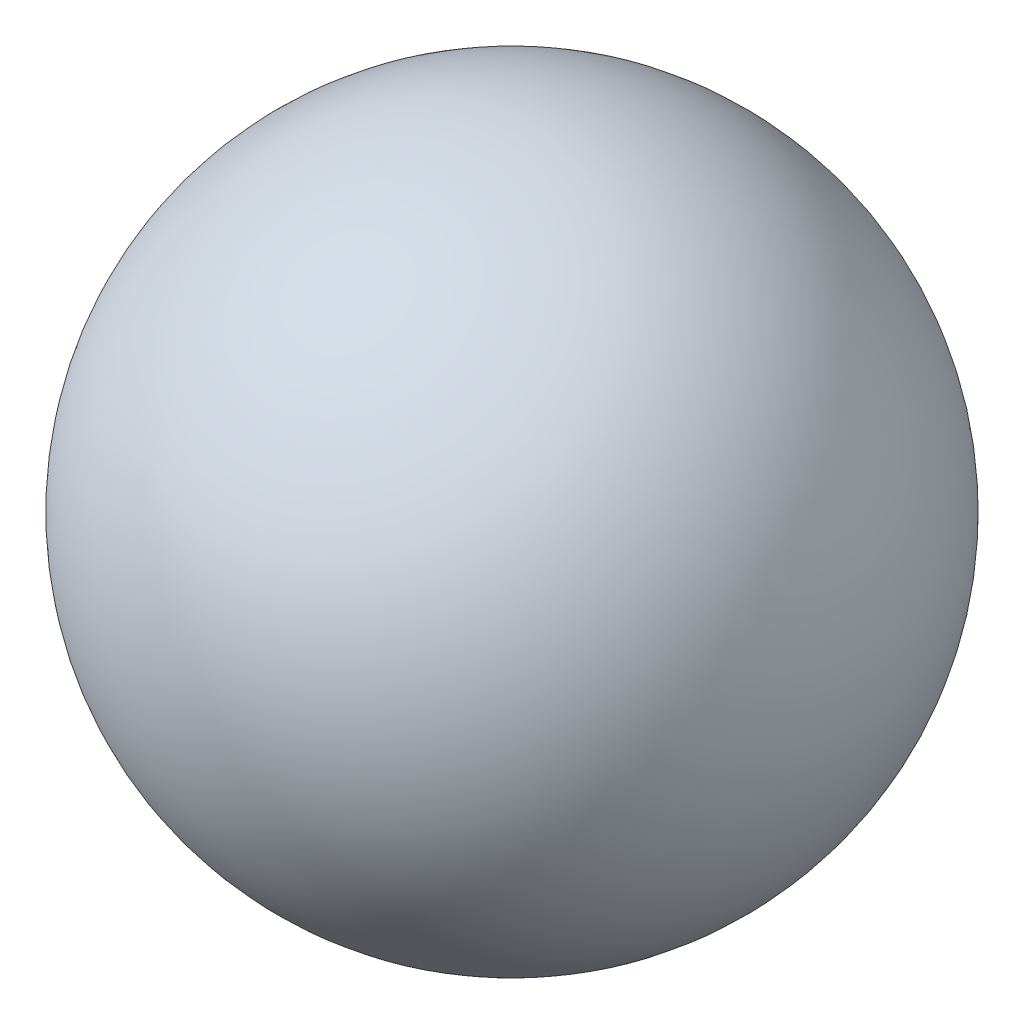
SolidWorks part; units mm, degrees
ref_plane "Front Plane" through (0, 0, 0) normal (0, 0, 1) x (1, 0, 0)
ref_plane "Top Plane" through (0, 0, 0) normal (0, 1, 0) x (1, 0, 0)
ref_plane "Right Plane" through (0, 0, 0) normal (1, 0, 0) x (0, 0, -1)
sketch "Sketch1" plane through (0, 0, 0) normal (0, 0, 1) x (1, 0, 0)
  line L0 (0, -8) -> (0, 8)
  arc A0 (0, 8) -> (0, -8) centre (0, 0) cw
  dimension "D1" = 8
revolve "Revolve1" add sketch "Sketch1" angle 360 about L0
